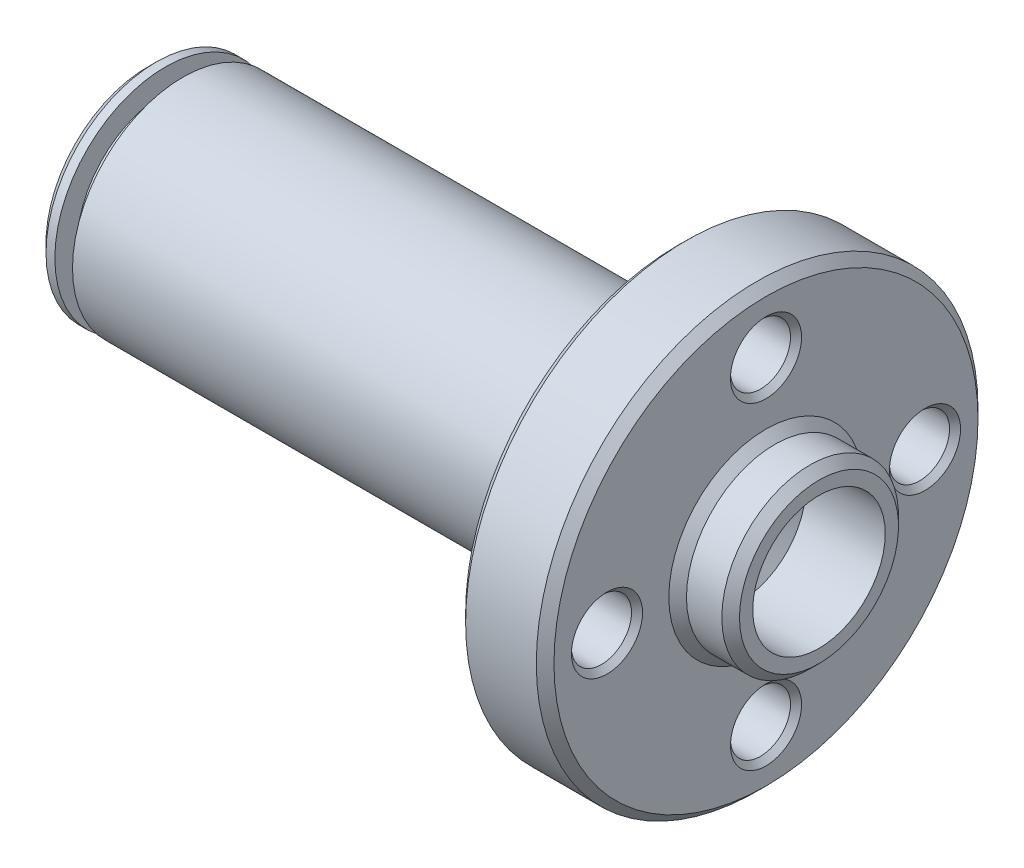
SolidWorks part; units mm, degrees
material "1.2210 (115CrV3)"
ref_plane "Front Plane" through (0, 0, 0) normal (0, 0, 1) x (1, 0, 0)
ref_plane "Top Plane" through (0, 0, 0) normal (0, 1, 0) x (1, 0, 0)
ref_plane "Right Plane" through (0, 0, 0) normal (1, 0, 0) x (0, 0, -1)
sketch "Sketch1" plane through (0, 0, 0) normal (0, 0, 1) x (1, 0, 0)
  line L0 (0, 6) -> (0, 12.5)
  line L1 (0, 12.5) -> (2, 12.5)
  line L2 (2, 12.5) -> (2, 10)
  line L3 (2, 10) -> (4, 10)
  line L4 (4, 10) -> (4, 12.5)
  line L5 (4, 12.5) -> (56.7, 12.5)
  line L6 (60, 16.5) -> (56.7, 16.5)
  line L7 (0, 6) -> (25, 6)
  line L8 (60, 16.5) -> (60, 25)
  line L9 (60, 25) -> (70, 25)
  line L10 (70, 25) -> (70, 10)
  line L11 (76, 0) -> (28.7492, 0)
  line L12 (-14.4608, 0) -> (0, 0) construction
  line L13 (70, 10) -> (76, 10)
  line L14 (76, 10) -> (76, 0)
  line L16 (25, 6) -> (28.7492, 0)
  line L17 (56.7, 16.5) -> (56.7, 12.5)
  dimension "D1" = 25
  dimension "D2" = 76
  dimension "D3" = 2
  dimension "D4" = 2
  dimension "D5" = 20
  dimension "D6" = 58
  dimension "D7" = 12
  dimension "D8" = 50
  dimension "D9" = 10
  dimension "D10" = 6
  dimension "D11" = 20
  dimension "D14" = 25
  dimension "D15" = 3.3
  dimension "D16" = 33
revolve "Revolve1" add sketch "Sketch1" angle 360 about L12
chamfer "Chamfer1" distance 1 angle 45 9 edges at (70, 0, 25) (60, 0, 25) (0, 0, 12.5) (76, 0, 10) (70, 0, 10) (0, 0, 6) (60, 0, 16.5) (56.7, 0, 16.5) (56.7, 0, 12.5)
hole_wizard "M8 Tapped Hole1" positions "Sketch4" profile "Sketch3" tap size "M8" standard "ISO" end condition through all
sketch "Sketch4" plane through (70, 0, 0) normal (1, 0, 0) x (0, 0, -1)
  line L0 (-18, 0) -> (0, 18) construction
  line L1 (0, 18) -> (18, 0) construction
  line L2 (18, 0) -> (0, -18) construction
  line L3 (0, -18) -> (-18, 0) construction
  line L4 (-18, 0) -> (0, 0) construction
  line L5 (0, 0) -> (0, 18) construction
  line L6 (0, 18) -> (18, 0) construction
  line L7 (18, 0) -> (0, 0) construction
  line L8 (0, 0) -> (0, -18) construction
  point P0 (0, 18)
  point P2 (18, 0)
  point P4 (-18, 0)
  point P6 (0, -18)
  dimension "D1" = 18
  dimension "D2" = 90
sketch "Sketch3" plane through (70, 18, 0) normal (0, 1, 0) x (0, 0, -1)
  line L0 (0, 0) -> (0, 70)
  line L1 (0, 70) -> (3.4, 70)
  line L2 (3.4, 70) -> (3.4, 0.625)
  line L3 (3.4, 0.625) -> (4.025, 0)
  line L5 (4.025, 0) -> (0, 0)
  line L6 (-3.4, 0.625) -> (-4.025, 0) construction
  line L11 (0, -6.35) -> (0, 107.95) construction
  dimension "Thread Major Dia." = 6.8
  dimension "Thru Tap Drill Depth" = 70
  dimension "Near C'Sink Dia." = 8.05
  dimension "Near C'Sink Angle" = 90
hole_wizard "Ø15.0 (15) Diameter Hole1" positions "Sketch6" profile "Sketch5" hole size "Ø15.0" standard "ISO"
sketch "Sketch6" plane through (76, 0, 0) normal (1, 0, 0) x (0, 0, -1)
  point P0 (0, 0)
sketch "Sketch5" plane through (76, 0, 0) normal (0, 1, 0) x (0, 0, -1)
  line L0 (0, 0) -> (0, 13.5065)
  line L1 (0, 13.5065) -> (7.5, 9)
  line L2 (7.5, 9) -> (7.5, 0)
  line L5 (7.5, 0) -> (0, 0)
  line L10 (0, 13.5065) -> (-7.5, 9) construction
  line L11 (0, -6.35) -> (0, 107.95) construction
  dimension "Hole Dia." = 15
  dimension "Hole Depth" = 9
  dimension "Drill Angle" = 118
